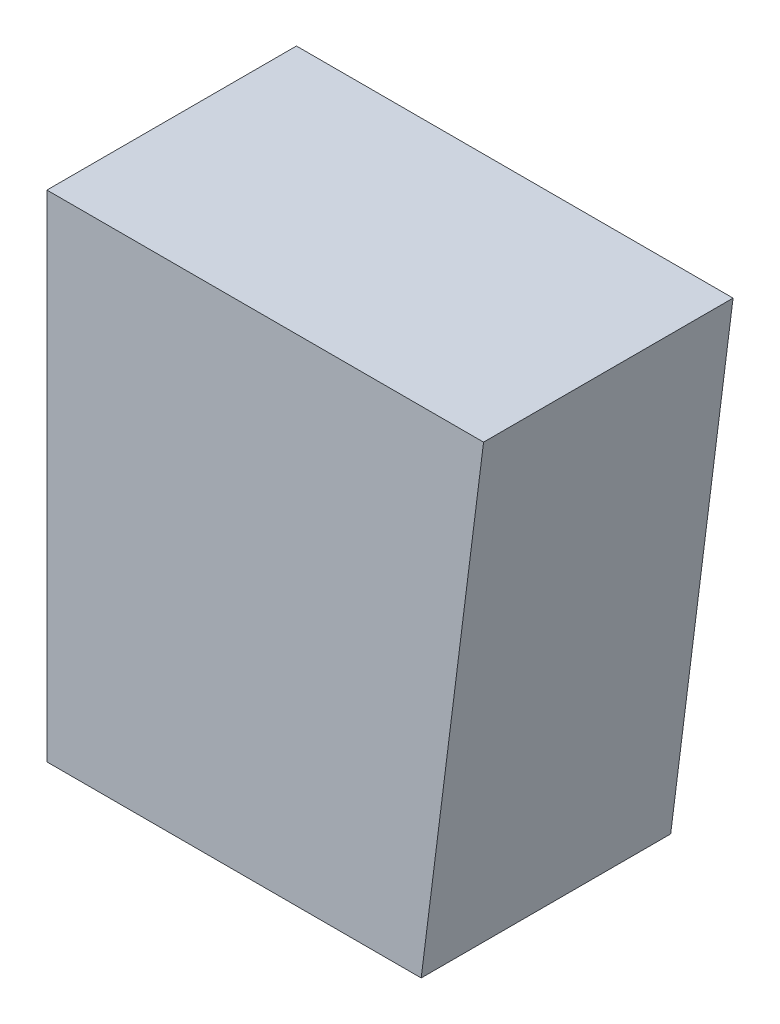
SolidWorks part; units mm, degrees
ref_plane "Front Plane" through (0, 0, 0) normal (0, 0, 1) x (1, 0, 0)
ref_plane "Top Plane" through (0, 0, 0) normal (0, 1, 0) x (1, 0, 0)
ref_plane "Right Plane" through (0, 0, 0) normal (1, 0, 0) x (0, 0, -1)
sketch "Sketch1" plane through (0, 0, 0) normal (0, 0, 1) x (1, 0, 0)
  line L0 (0, 0) -> (7.62, 0)
  line L5 (7.62, 0) -> (8.89, 10.0838)
  line L6 (8.89, 10.0838) -> (0, 10.0838)
  line L7 (0, 10.0838) -> (0, 0)
  dimension "D1" = 7.62
  dimension "D2" = 10.0838
  dimension "D3" = 8.89
extrude "Boss-Extrude1" add sketch "Sketch1" along normal blind 5.08
